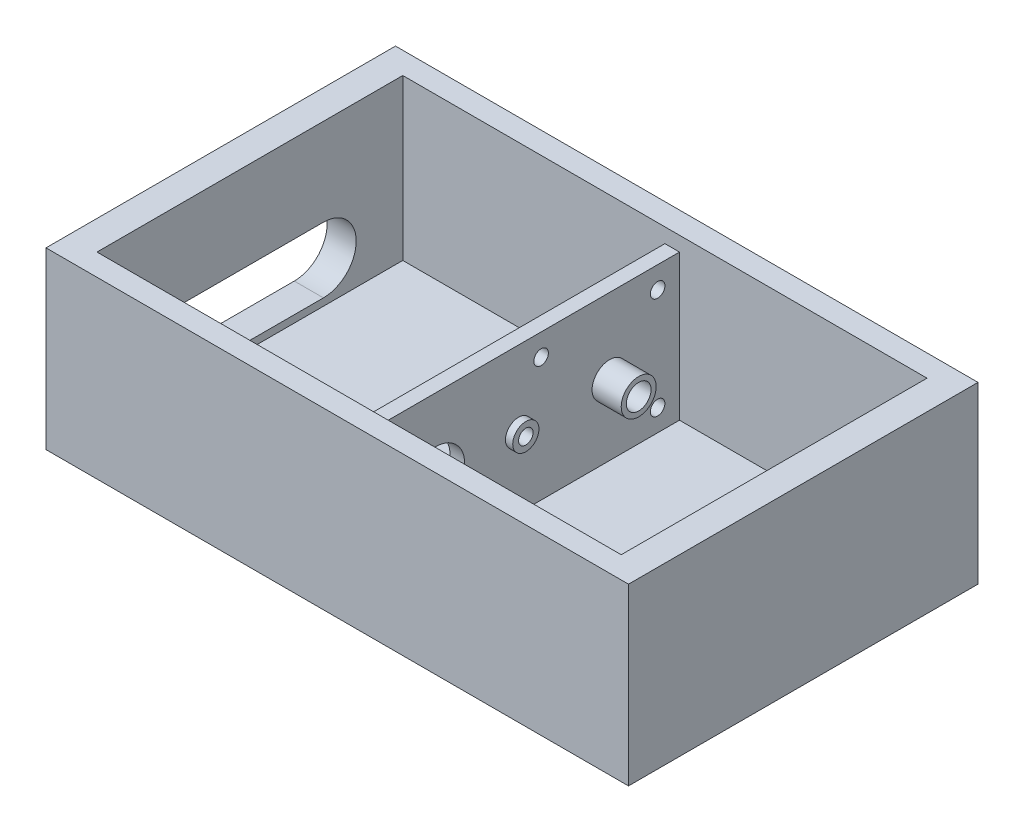
SolidWorks part; units mm, degrees
ref_plane "前视基准面" through (0, 0, 0) normal (0, 0, 1) x (1, 0, 0)
ref_plane "上视基准面" through (0, 0, 0) normal (0, 1, 0) x (1, 0, 0)
ref_plane "右视基准面" through (0, 0, 0) normal (1, 0, 0) x (0, 0, -1)
sketch "草图2" plane through (0, 0, 0) normal (1, 0, 0) x (0, 0, -1)
  line L1 (-12, 6) -> (12, 6)
  line L2 (-12, 6) -> (-12, -6)
  line L3 (-12, -6) -> (12, -6)
  line L4 (12, 6) -> (12, -6)
  line L5 (-12, 6) -> (12, -6) construction
  line L6 (-12, -6) -> (12, 6) construction
  point P0 (0, 0)
  dimension "D1" = 12
  dimension "D2" = 24
extrude "凸台-拉伸1" add sketch "草图2" along normal blind 40
sketch "草图3" plane through (0, 6, 0) normal (0, 1, 0) x (1, 0, 0)
  line L0 (0, 12) -> (0, -12) construction
  line L1 (2, 10.5) -> (38, 10.5)
  line L2 (2, 10.5) -> (2, -10.5)
  line L3 (2, -10.5) -> (38, -10.5)
  line L4 (38, 10.5) -> (38, -10.5)
  line L5 (40, 12) -> (0, 12) construction
  line L6 (40, 12) -> (40, -12) construction
  line L7 (40, -12) -> (0, -12) construction
  dimension "D1" = 2
  dimension "D2" = 1.5
  dimension "D3" = 2
  dimension "D4" = 1.5
extrude "切除-拉伸1" cut sketch "草图3" against normal blind 11
sketch "草图4" plane through (0, 0, 0) normal (-1, 0, 0) x (0, 0, 1)
  line L0 (-5.05, -2.25) -> (6.45, -2.25) construction
  line L1 (-5.05, 0) -> (6.45, 0)
  line L2 (-5.05, -4.5) -> (6.45, -4.5)
  line L6 (12, 6) -> (12, -6) construction
  line L7 (-12, 6) -> (12, 6) construction
  arc A0 (-5.05, 0) -> (-5.05, -4.5) centre (-5.05, -2.25) ccw
  arc A1 (6.45, -4.5) -> (6.45, 0) centre (6.45, -2.25) ccw
  point P2 (0.7, -2.25)
  point P7 (8.7, -2.25)
  point P8 (-7.3, -2.25)
  dimension "D2" = 16
  dimension "D1" = 11.5
  dimension "D3" = 3.3
  dimension "D4" = 6
extrude "切除-拉伸2" cut sketch "草图4" against normal blind 2
sketch "草图7" plane through (0, -5, 0) normal (0, 1, 0) x (1, 0, 0)
  line L0 (38, 10.5) -> (2, 10.5) construction
  line L1 (20, 10.5) -> (21, 10.5)
  line L2 (20, 10.5) -> (20, -10.5)
  line L3 (20, -10.5) -> (21, -10.5)
  line L4 (21, 10.5) -> (21, -10.5)
  line L5 (2, -10.5) -> (38, -10.5) construction
  line L6 (2, 10.5) -> (2, -10.5) construction
  dimension "D1" = 18
  dimension "D2" = 1
extrude "凸台-拉伸4" add sketch "草图7" along normal blind 10
sketch "草图8" plane through (20, 0, 0) normal (-1, 0, 0) x (0, 0, 1)
  line L1 (12, -6) -> (-12, -6) construction
  line L2 (-12, -6) -> (-12, 6) construction
  circle A0 centre (-5.7, -0.2) radius 0.85
  dimension "D3" = 1.7
  dimension "D1" = 5.8
  dimension "D2" = 6.3
extrude "切除-拉伸3" cut sketch "草图8" against normal blind 3
sketch "草图9" plane through (21, 0, 0) normal (1, 0, 0) x (0, 0, -1)
  circle A0 centre (5.7, -0.2) radius 1.2
  dimension "D1" = 2.4
extrude "凸台-拉伸5" add sketch "草图9" along normal blind 2
sketch "草图10" plane through (23, 0, 0) normal (1, 0, 0) x (0, 0, -1)
  circle A0 centre (5.7, -0.2) radius 0.85
  dimension "D1" = 1.7
extrude "切除-拉伸4" cut sketch "草图10" against normal blind 2
sketch "草图11" plane through (21, 0, 0) normal (1, 0, 0) x (0, 0, -1)
  line L0 (-10.5, -5) -> (10.5, -5) construction
  circle A0 centre (-0.55, -0.2) radius 0.9
  circle A1 centre (5.7, -0.2) radius 1.2 construction
  dimension "D1" = 1.8
  dimension "D2" = 6.25
  dimension "D3" = 4.8
extrude "凸台-拉伸6" add sketch "草图11" along normal blind 0.5
sketch "草图12" plane through (21.5, 0, 0) normal (1, 0, 0) x (0, 0, -1)
  circle A0 centre (-0.55, -0.2) radius 0.5
  dimension "D1" = 1
extrude "切除-拉伸5" cut sketch "草图12" against normal blind 2 and the other way blind 17
sketch "草图13" plane through (21, 0, 0) normal (1, 0, 0) x (0, 0, -1)
  line L0 (-10.5, -5) -> (10.5, -5) construction
  circle A0 centre (-6.25, -0.2) radius 2
  circle A1 centre (-0.55, -0.2) radius 0.9 construction
  dimension "D1" = 4
  dimension "D2" = 5.7
  dimension "D3" = 4.8
extrude "切除-拉伸6" cut sketch "草图13" against normal blind 2
sketch "草图14" plane through (21, 0, 0) normal (1, 0, 0) x (0, 0, -1)
  line L0 (-10.5, -5) -> (10.5, -5) construction
  line L1 (10.5, 5) -> (10.5, -5) construction
  line L2 (-10.5, 5) -> (10.5, 5) construction
  circle A0 centre (9, -3.5) radius 0.5
  circle A1 centre (9, 3.5) radius 0.5
  circle A2 centre (1, 3.5) radius 0.5
  dimension "D1" = 1
  dimension "D4" = 1
  dimension "D7" = 1
  dimension "D2" = 1.5
  dimension "D3" = 1.5
  dimension "D5" = 1.5
  dimension "D6" = 1.5
  dimension "D8" = 8
  dimension "D9" = 1.5
extrude "切除-拉伸7" cut sketch "草图14" against normal blind 2
